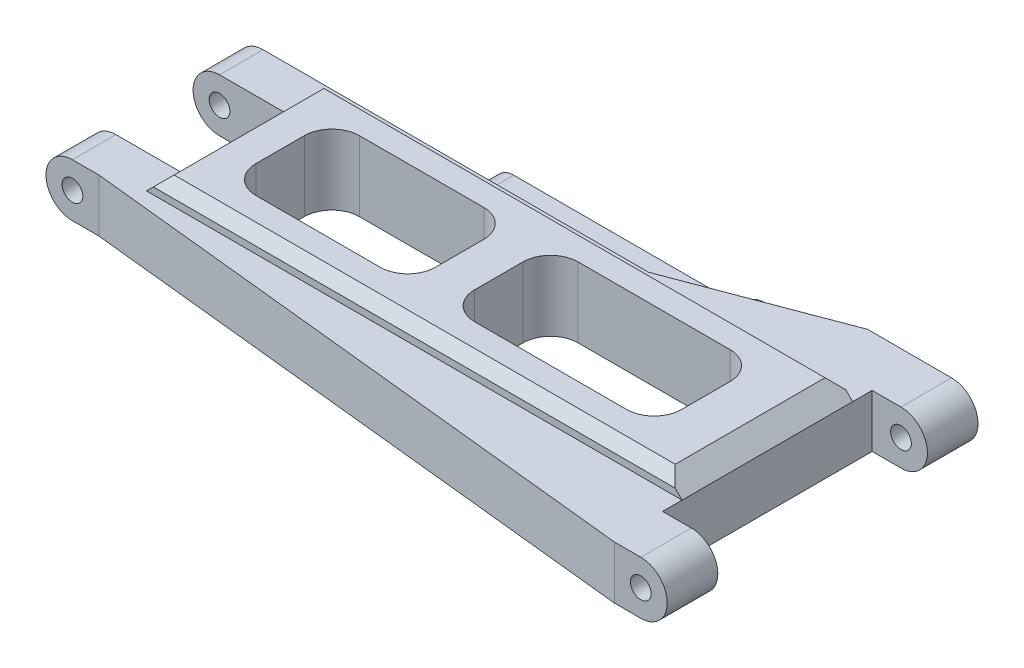
SolidWorks part; units mm, degrees
ref_plane "Front Plane" through (0, 0, 0) normal (0, 0, 1) x (1, 0, 0)
ref_plane "Top Plane" through (0, 0, 0) normal (0, 1, 0) x (1, 0, 0)
ref_plane "Right Plane" through (0, 0, 0) normal (1, 0, 0) x (0, 0, -1)
sketch "Sketch1" plane through (0, 0, 0) normal (0, 0, 1) x (1, 0, 0)
  line L0 (-45.5, 0) -> (45.5, 0) construction
  line L1 (-45.5, 3.83) -> (45.5, 3.83)
  line L2 (-45.5, -3.83) -> (45.5, -3.83)
  arc A0 (-45.5, 3.83) -> (-45.5, -3.83) centre (-45.5, 0) ccw
  arc A1 (45.5, -3.83) -> (45.5, 3.83) centre (45.5, 0) ccw
  circle A2 centre (-45.5, 0) radius 1.5
  circle A3 centre (45.5, 0) radius 1.5
  point P2 (0, 0)
  dimension "D3" = 3
  dimension "D1" = 7.66
  dimension "D2" = 91
extrude "Boss-Extrude1" add sketch "Sketch1" along normal mid plane 45
sketch "Sketch2" plane through (0, 3.83, 0) normal (0, 1, 0) x (1, 0, 0)
  line L0 (-41.67, -22.5) -> (41.67, -13.8)
  line L1 (45.5, -22.5) -> (-45.5, -22.5) construction
  line L2 (41.67, -13.8) -> (49.33, -13.8)
  line L3 (49.33, -22.5) -> (49.33, 22.5) construction
  line L4 (49.33, -13.8) -> (49.33, -22.5)
  line L5 (49.33, -22.5) -> (-41.67, -22.5)
  line L6 (-49.33, -22.5) -> (-45.5, -22.5) construction
  line L7 (-49.33, -22.5) -> (-45.5, -22.5)
  line L8 (-41.67, -22.5) -> (-45.5, -22.5)
  line L9 (45.5, -22.5) -> (49.33, -22.5) construction
  line L10 (45.5, -22.5) -> (49.33, -22.5)
  line L11 (45.5, -13.8) -> (41.67, -13.8)
  line L12 (-33.33, 22.5) -> (-10.33, 13.8)
  line L13 (45.5, 22.5) -> (-45.5, 22.5) construction
  line L14 (-10.33, 13.8) -> (49.33, 13.8)
  line L15 (49.33, 13.8) -> (49.33, 22.5)
  line L16 (49.33, 22.5) -> (-33.33, 22.5)
  line L17 (-49.33, 22.5) -> (-49.33, -22.5) construction
  line L19 (-6.43, 7.5) -> (-28.43, 7.5)
  line L20 (-2.43, 3.5) -> (-2.43, -3.5)
  line L21 (-6.43, -7.5) -> (-28.43, -7.5)
  line L22 (-32.43, 3.5) -> (-32.43, -3.5)
  line L23 (-2.43, 7.5) -> (-32.43, -7.5) construction
  line L24 (-2.43, -7.5) -> (-32.43, 7.5) construction
  line L25 (-41.33, -15.175) -> (-49.33, -15.175)
  line L26 (-41.33, -15.175) -> (-41.33, 15.175)
  line L27 (-41.33, 15.175) -> (-49.33, 15.175)
  line L28 (-49.33, -15.175) -> (-49.33, 15.175)
  line L29 (-41.33, -15.175) -> (-49.33, 15.175) construction
  line L30 (-41.33, 15.175) -> (-49.33, -15.175) construction
  line L31 (25.23, -7.5) -> (7.23, -7.5)
  line L32 (29.23, -3.5) -> (29.23, 3.5)
  line L33 (25.23, 7.5) -> (7.23, 7.5)
  line L34 (3.23, -3.5) -> (3.23, 3.5)
  line L35 (29.23, -7.5) -> (3.23, 7.5) construction
  line L36 (29.23, 7.5) -> (3.23, -7.5) construction
  line L37 (36.23, -7.5) -> (49.33, -7.5)
  line L38 (36.23, -7.5) -> (36.23, 7.5)
  line L39 (36.23, 7.5) -> (49.33, 7.5)
  line L40 (49.33, -7.5) -> (49.33, 7.5)
  line L41 (36.23, -7.5) -> (49.33, 7.5) construction
  line L42 (36.23, 7.5) -> (49.33, -7.5) construction
  arc A0 (-6.43, 7.5) -> (-2.43, 3.5) centre (-6.43, 3.5) cw
  arc A1 (-2.43, -3.5) -> (-6.43, -7.5) centre (-6.43, -3.5) cw
  arc A2 (-28.43, -7.5) -> (-32.43, -3.5) centre (-28.43, -3.5) cw
  arc A3 (-28.43, 7.5) -> (-32.43, 3.5) centre (-28.43, 3.5) ccw
  arc A4 (29.23, 3.5) -> (25.23, 7.5) centre (25.23, 3.5) ccw
  arc A5 (25.23, -7.5) -> (29.23, -3.5) centre (25.23, -3.5) ccw
  arc A6 (7.23, -7.5) -> (3.23, -3.5) centre (7.23, -3.5) cw
  arc A7 (7.23, 7.5) -> (3.23, 3.5) centre (7.23, 3.5) ccw
  point P23 (-17.43, 0)
  point P41 (-45.33, 0)
  point P47 (16.23, 0)
  point P62 (42.78, 0)
  line M11 (45.5, 22.5) -> (-45.5, 22.5)
  line M13 (-45.5, -22.5) -> (45.5, -22.5)
  line M14 (45.5, -22.5) -> (45.5, 22.5)
  dimension "D5" = 4
  dimension "D11" = 4
  dimension "D1" = 13.8
  dimension "D2" = 13.8
  dimension "D3" = 16
  dimension "D4" = 39
  dimension "D6" = 30
  dimension "D7" = 15
  dimension "D8" = 30.35
  dimension "D9" = 8
  dimension "D10" = 8.9
  dimension "D12" = 5.66
  dimension "D13" = 26
  dimension "D14" = 7
extrude "Cut-Extrude1" cut sketch "Sketch2" against normal through all contours L12 L14 M14 M11 | L2 L0 M13 M14 | L5 L4 L2 M14 | L15 L16 L14 M14 | L19 A3 L22 A2 L21 A1 L20 A0 | L33 A7 L34 A6 L31 A5 L32 A4 | L26 L27 L28 L25 | L37 L40 L39 L38
sketch "Sketch3" plane through (0, 0, 0) normal (0, 1, 0) x (1, 0, 0)
  line L0 (-41.33, -15.175) -> (-41.33, 15.175) construction
  line L1 (-41.33, -12.35) -> (36.23, -12.35)
  line L2 (-41.33, -12.35) -> (-41.33, 12.35)
  line L3 (-41.33, 12.35) -> (36.23, 12.35)
  line L4 (36.23, -12.35) -> (36.23, 12.35)
  line L5 (-41.33, -12.35) -> (36.23, 12.35) construction
  line L6 (-41.33, 12.35) -> (36.23, -12.35) construction
  line L7 (36.23, -7.5) -> (36.23, 7.5) construction
  line L13 (-6.43, 7.5) -> (-28.43, 7.5)
  line L14 (-2.43, -3.5) -> (-2.43, 3.5)
  line L15 (-28.43, -7.5) -> (-6.43, -7.5)
  line L16 (-32.43, 3.5) -> (-32.43, -3.5)
  line L17 (-6.43, 7.5) -> (-28.43, 7.5)
  line L18 (-2.43, -3.5) -> (-2.43, 3.5)
  line L19 (-28.43, -7.5) -> (-6.43, -7.5)
  line L20 (-32.43, 3.5) -> (-32.43, -3.5)
  line L21 (25.23, 7.5) -> (7.23, 7.5)
  line L22 (29.23, -3.5) -> (29.23, 3.5)
  line L23 (7.23, -7.5) -> (25.23, -7.5)
  line L24 (3.23, 3.5) -> (3.23, -3.5)
  line L25 (25.23, 7.5) -> (7.23, 7.5)
  line L26 (29.23, -3.5) -> (29.23, 3.5)
  line L27 (7.23, -7.5) -> (25.23, -7.5)
  line L28 (3.23, 3.5) -> (3.23, -3.5)
  arc A4 (-28.43, 7.5) -> (-32.43, 3.5) centre (-28.43, 3.5) ccw
  arc A5 (-2.43, 3.5) -> (-6.43, 7.5) centre (-6.43, 3.5) ccw
  arc A6 (-6.43, -7.5) -> (-2.43, -3.5) centre (-6.43, -3.5) ccw
  arc A7 (-32.43, -3.5) -> (-28.43, -7.5) centre (-28.43, -3.5) ccw
  arc A8 (-28.43, 7.5) -> (-32.43, 3.5) centre (-28.43, 3.5) ccw
  arc A9 (-2.43, 3.5) -> (-6.43, 7.5) centre (-6.43, 3.5) ccw
  arc A10 (-6.43, -7.5) -> (-2.43, -3.5) centre (-6.43, -3.5) ccw
  arc A11 (-32.43, -3.5) -> (-28.43, -7.5) centre (-28.43, -3.5) ccw
  arc A12 (7.23, 7.5) -> (3.23, 3.5) centre (7.23, 3.5) ccw
  arc A13 (29.23, 3.5) -> (25.23, 7.5) centre (25.23, 3.5) ccw
  arc A14 (25.23, -7.5) -> (29.23, -3.5) centre (25.23, -3.5) ccw
  arc A15 (3.23, -3.5) -> (7.23, -7.5) centre (7.23, -3.5) ccw
  arc A16 (7.23, 7.5) -> (3.23, 3.5) centre (7.23, 3.5) ccw
  arc A17 (29.23, 3.5) -> (25.23, 7.5) centre (25.23, 3.5) ccw
  arc A18 (25.23, -7.5) -> (29.23, -3.5) centre (25.23, -3.5) ccw
  arc A19 (3.23, -3.5) -> (7.23, -7.5) centre (7.23, -3.5) ccw
  point P0 (-2.55, 0)
  dimension "D1" = 24.7
  dimension "D2" = 0
  dimension "D3" = 0
extrude "Boss-Extrude2" add sketch "Sketch3" along normal offset from surface (6.33 mm away) 2.5 contours L1 L4 L3 L2 A19 L28 A16 L25 A17 L26 A18 L27 A11 L20 A8 L17 A9 L18 A10 L19 up to face at (-17.43, 3.83, 0) offset beyond the face yes
chamfer "Chamfer1" distance 2.5 angle 45 2 edges at (36.23, 6.33, 0) (-41.33, 6.33, 0)
chamfer "Chamfer2" distance 1.5 angle 45 2 edges at (-2.55, 6.33, -12.35) (-2.55, 6.33, 12.35)
sketch "Sketch4" plane through (0, 0, -13.8) normal (0, 0, -1) x (-1, 0, 0)
  line L0 (21.5, 0) -> (-12.5, 0) construction
  line L1 (21.5, -2.93) -> (-12.5, -2.93)
  line L2 (21.5, 2.93) -> (-12.5, 2.93)
  arc A0 (21.5, -2.93) -> (21.5, 2.93) centre (21.5, 0) ccw
  arc A1 (-12.5, 2.93) -> (-12.5, -2.93) centre (-12.5, 0) ccw
  point P2 (4.5, 0)
  point P10 (45.5, 0)
  dimension "D1" = 5.86
  dimension "D2" = 34
  dimension "D3" = 58
extrude "Boss-Extrude3" add sketch "Sketch4" along normal offset from surface (3.31 mm away) 4.76 up to face at (-2.55, 4.33, -12.35) offset beyond the face yes
sketch "Sketch5" plane through (0, 0, -17.11) normal (0, 0, -1) x (-1, 0, 0)
  circle A0 centre (21.5, 0) radius 3
  dimension "D1" = 6
extrude "Boss-Extrude4" add sketch "Sketch5" along normal blind 2.4
fillet "Fillet1" radius 0.5 1 edges at (-24.5, 0, -19.51)
sketch "Sketch6" plane through (0, 0, -19.51) normal (0, 0, -1) x (-1, 0, 0)
  line L0 (21.5, 0) -> (-12.5, 0) construction
  line L1 (-5.3, 0) -> (-12.5, 0) construction
  circle A0 centre (21.5, 0) radius 1.25
  circle A1 centre (9.1, 0) radius 1.25
  circle A2 centre (1.9, 0) radius 1.25
  circle A3 centre (-5.3, 0) radius 1.25
  circle A4 centre (-12.5, 0) radius 1.25
  circle A5 centre (-8.9, 0) radius 1.25
  dimension "D3" = 2.5
  dimension "D2" = 12.4
  dimension "D1" = 4
extrude "Cut-Extrude2" cut sketch "Sketch6" against normal blind 10
mirror "Mirror1" about plane through (0, 0, 0) normal (1, 0, 0) of bodies 106
delete or keep bodies "Body-Delete/Keep 1" type keep bodies bodies 107
